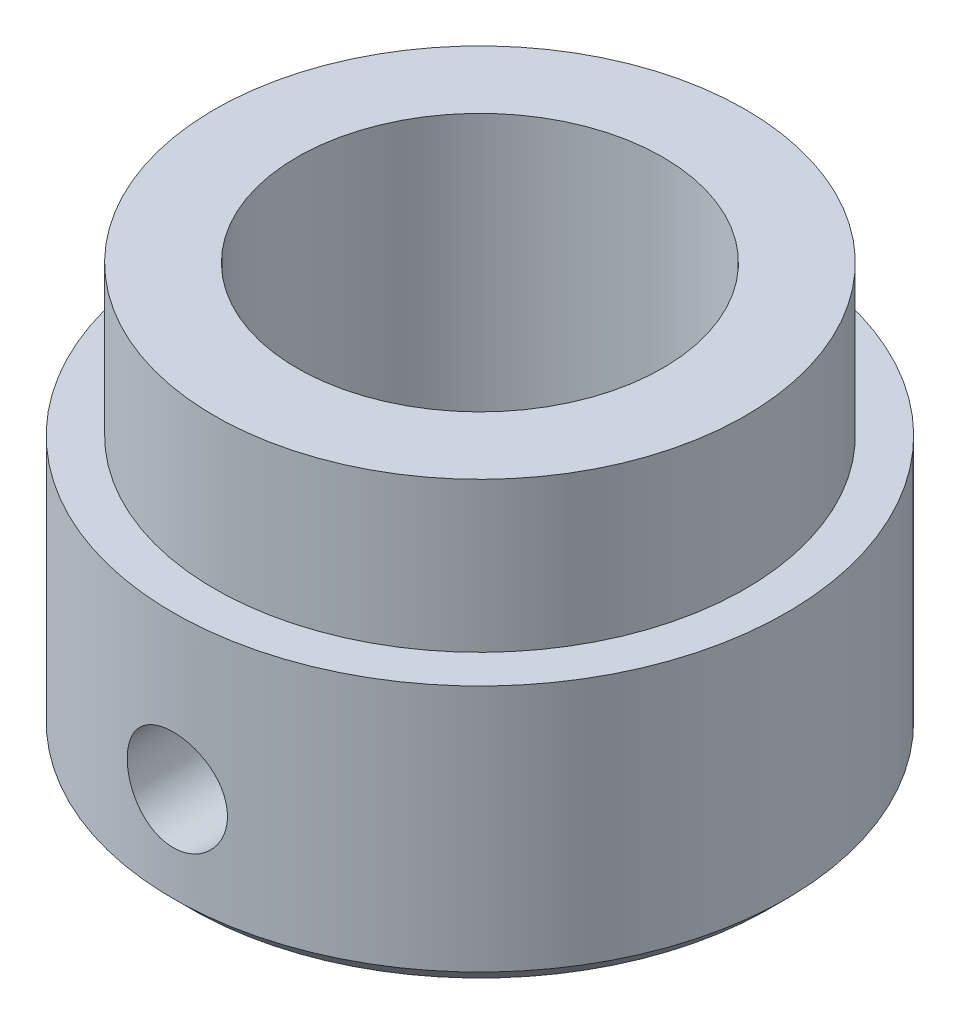
SolidWorks part; units mm, degrees
material "AISI 1020"
ref_plane "Plano frontal" through (0, 0, 0) normal (0, 0, 1) x (1, 0, 0)
ref_plane "Plano superior" through (0, 0, 0) normal (0, 1, 0) x (1, 0, 0)
ref_plane "Plano direito" through (0, 0, 0) normal (1, 0, 0) x (0, 0, -1)
sketch "Esboço1" plane through (0, 0, 0) normal (1, 0, 0) x (0, 0, -1)
  line L0 (0, 0) -> (0, 35.2) construction
  line L1 (15.5, 35.2) -> (15.5, 0)
  line L2 (15.5, 0) -> (24.5, 0)
  line L3 (26, 1.5) -> (26, 22.5)
  line L4 (26, 22.5) -> (22.5, 22.5)
  line L5 (22.5, 22.5) -> (22.5, 35.2)
  line L6 (22.5, 35.2) -> (15.5, 35.2)
  line L7 (24.5, 0) -> (26, 1.5)
  point P5 (0, 0)
  point P6 (26, 0)
  point P10 (0, 0)
  dimension "D1" = 35.2
  dimension "D2" = 52
  dimension "D3" = 22.5
  dimension "D4" = 45
  dimension "D5" = 31
revolve "Revolução1" add sketch "Esboço1" angle 360 about L0
sketch "Esboço2" plane through (0, 0, 0) normal (0, 0, 1) x (1, 0, 0)
  line L0 (0, 0) -> (0, 9.5) construction
  circle A0 centre (0, 9.5) radius 4.25
  dimension "D1" = 8.5
  dimension "D2" = 9.5
extrude "Corte-extrusão1" cut sketch "Esboço2" against normal through all both and the other way through all
